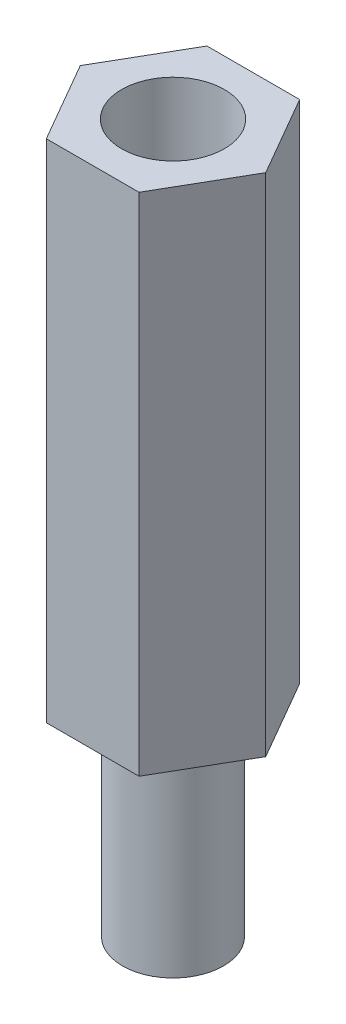
SolidWorks part; units mm, degrees
ref_plane "Спереди" through (0, 0, 0) normal (0, 0, 1) x (1, 0, 0)
ref_plane "Сверху" through (0, 0, 0) normal (0, 1, 0) x (1, 0, 0)
ref_plane "Справа" through (0, 0, 0) normal (1, 0, 0) x (0, 0, -1)
sketch "Эскиз1" plane through (0, 0, 0) normal (0, 1, 0) x (1, 0, 0)
  circle A0 centre (0, 0) radius 1.5
  dimension "D1" = 3
extrude "Бобышка-Вытянуть1" add sketch "Эскиз1" along normal blind 6
sketch "Эскиз2" plane through (0, 6, 0) normal (0, 1, 0) x (1, 0, 0)
  line L1 (2.75, 0) -> (1.375, 2.3816)
  line L2 (1.375, 2.3816) -> (-1.375, 2.3816)
  line L3 (-1.375, 2.3816) -> (-2.75, 0)
  line L4 (-2.75, 0) -> (-1.375, -2.3816)
  line L5 (-1.375, -2.3816) -> (1.375, -2.3816)
  line L6 (1.375, -2.3816) -> (2.75, 0)
  circle A0 centre (0, 0) radius 2.3816 construction
  dimension "D1" = 5.5
extrude "Бобышка-Вытянуть2" add sketch "Эскиз2" along normal blind 15
hole_wizard "Сверло под метчик  спиральное #41" positions "Эскиз3" profile "Эскиз5" hole size "#4-40" standard "Ansi Inch"
sketch "Эскиз3" plane through (0, 21, 0) normal (0, 1, 0) x (1, 0, 0)
  point P0 (0, 0)
sketch "Эскиз5" plane through (0, 21, 0) normal (1, 0, 0) x (0, 0, 1)
  line L0 (0, 0) -> (0, 6.9157)
  line L1 (0, 6.9157) -> (1.524, 6)
  line L2 (1.524, 6) -> (1.524, 0)
  line L5 (1.524, 0) -> (0, 0)
  line L10 (0, 6.9157) -> (-1.524, 6) construction
  line L11 (0, -6.35) -> (0, 107.95) construction
  dimension "Диаметр отверстия" = 3.048
  dimension "Глубина отверстия" = 6
  dimension "Угол заточки сверла" = 118
